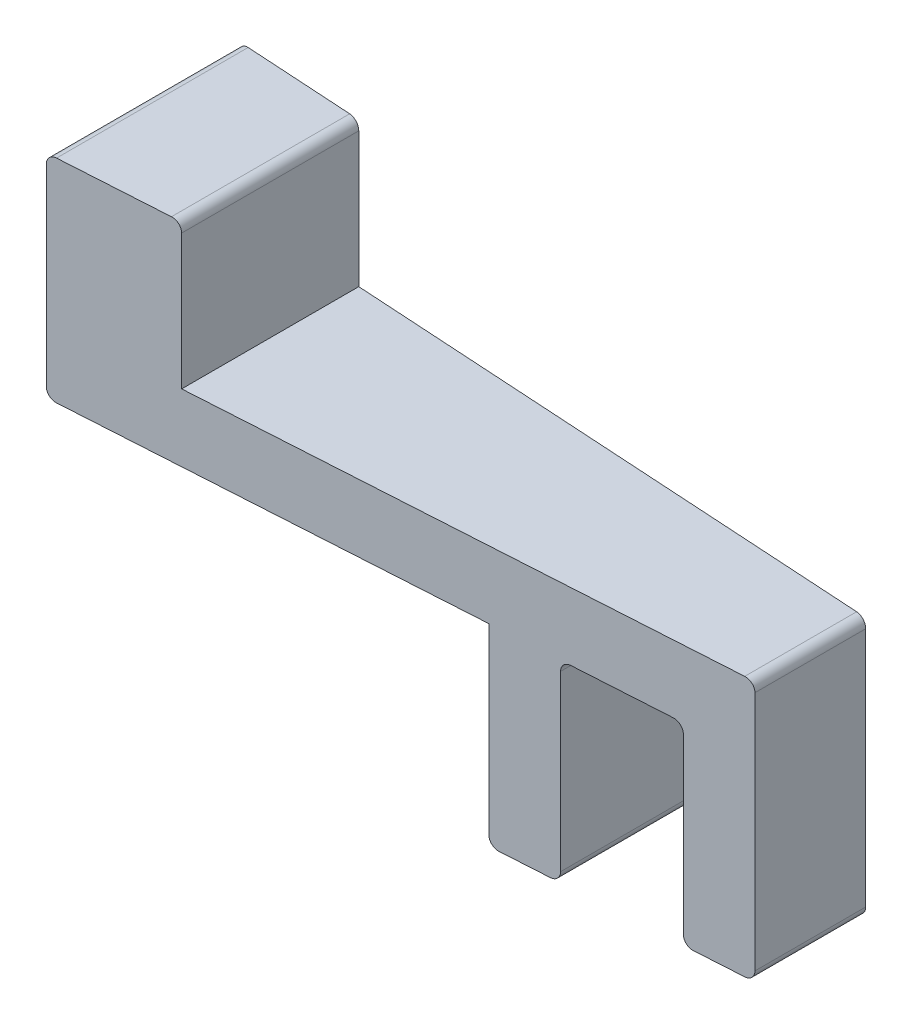
SolidWorks part; units mm, degrees
ref_plane "Спереди" through (0, 0, 0) normal (0, 0, 1) x (1, 0, 0)
ref_plane "Сверху" through (0, 0, 0) normal (0, 1, 0) x (1, 0, 0)
ref_plane "Справа" through (0, 0, 0) normal (1, 0, 0) x (0, 0, -1)
sketch "Эскиз1" plane through (0, 0, 0) normal (0, 0, 1) x (1, 0, 0)
  line L0 (0, 1) -> (0, 21)
  line L1 (1, 22) -> (12.2299, 22)
  line L2 (13.2299, 21) -> (13.2299, 7)
  line L3 (13.2299, 7) -> (41.2299, 7)
  line L4 (1, 0) -> (43.2657, 0)
  line L5 (43.2657, 0) -> (43.2657, -19)
  line L6 (44.2657, -20) -> (49.2657, -20)
  line L7 (50.2657, -19) -> (50.2657, -1)
  line L8 (51.2657, 0) -> (61.2657, 0)
  line L9 (62.2657, -1) -> (62.2657, -19)
  line L10 (63.2657, -20) -> (68.2657, -20)
  line L11 (69.2657, -19) -> (69.2657, 6)
  line L12 (68.2657, 7) -> (41.2299, 7)
  arc A0 (61.2657, 0) -> (62.2657, -1) centre (61.2657, -1) cw
  arc A1 (50.2657, -1) -> (51.2657, 0) centre (51.2657, -1) cw
  arc A2 (43.2657, -19) -> (44.2657, -20) centre (44.2657, -19) ccw
  arc A3 (49.2657, -20) -> (50.2657, -19) centre (49.2657, -19) ccw
  arc A4 (62.2657, -19) -> (63.2657, -20) centre (63.2657, -19) ccw
  arc A5 (68.2657, -20) -> (69.2657, -19) centre (68.2657, -19) ccw
  arc A6 (0, 1) -> (1, 0) centre (1, 1) ccw
  arc A7 (12.2299, 22) -> (13.2299, 21) centre (12.2299, 21) cw
  arc A8 (0, 21) -> (1, 22) centre (1, 21) cw
  arc A9 (69.2657, 6) -> (68.2657, 7) centre (68.2657, 6) ccw
  point P17 (62.2657, 0)
  point P20 (50.2657, 0)
  point P23 (43.2657, -20)
  point P26 (50.2657, -20)
  point P29 (62.2657, -20)
  point P32 (69.2657, -20)
  point P35 (0, 0)
  point P38 (13.2299, 22)
  point P41 (0, 22)
  dimension "1" = 1
  dimension "D9" = 1
  dimension "D1" = 20
  dimension "D2" = 7
  dimension "D3" = 28
  dimension "D4" = 20
  dimension "D5" = 12
  dimension "D6" = 7
  dimension "D7" = 7
  dimension "D8" = 20
extrude "Бобышка-Вытянуть1" add sketch "Эскиз1" along normal blind 20
sketch "Эскиз2" plane through (0, 22, 0) normal (0, 1, 0) x (1, 0, 0)
  line L0 (0, -10) -> (82.789, -10) construction
  line L1 (68.2657, -20) -> (13.2299, -20) construction
  line L2 (81.3929, -5) -> (0, 0)
  line L3 (81.3929, -15) -> (0, -20)
  line L4 (81.3929, -5) -> (88.4719, 13.8666)
  line L5 (88.4719, 13.8666) -> (0, 0)
  line L6 (81.3929, -15) -> (97.4934, -39.6829)
  line L7 (0, -20) -> (97.4934, -39.6829)
  dimension "D1" = 10
  dimension "D2" = 5
extrude "Вырез-Вытянуть1" cut sketch "Эскиз2" against normal blind 82
